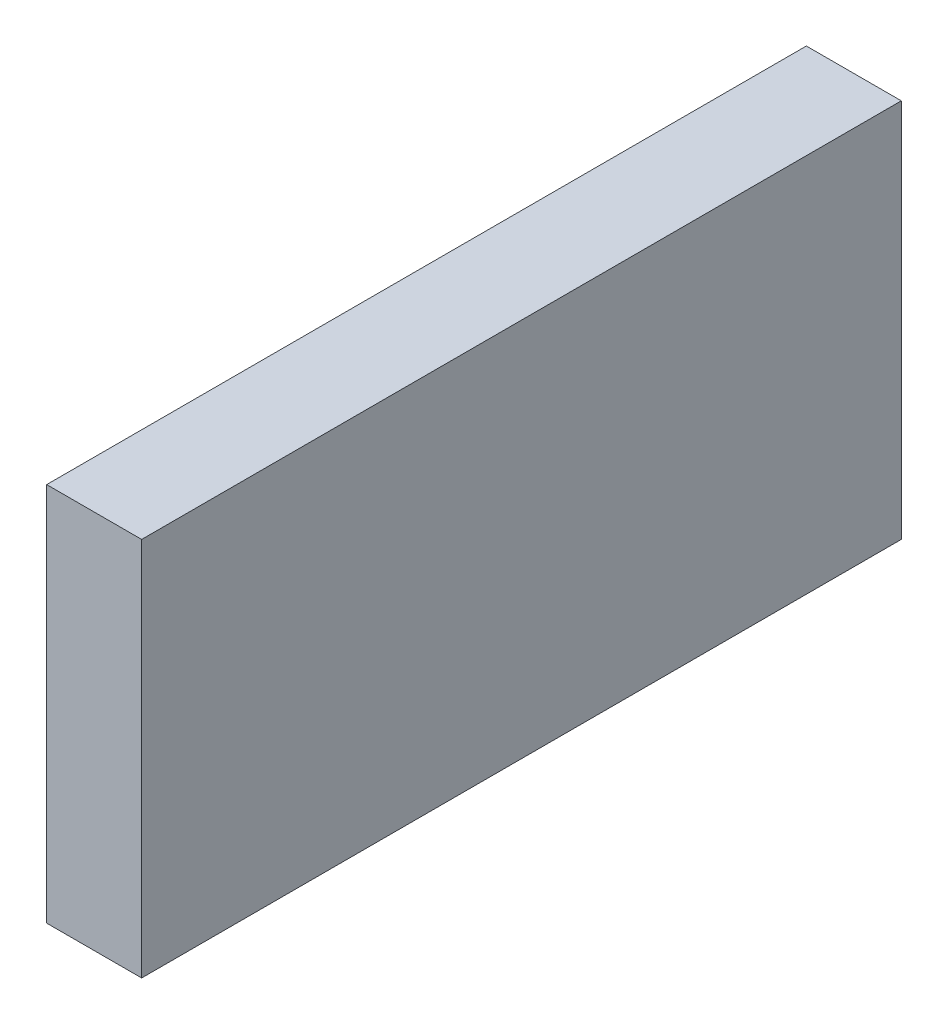
SolidWorks part; units mm, degrees
material "PE High Density"
ref_plane "Front Plane" through (0, 0, 0) normal (0, 0, 1) x (1, 0, 0)
ref_plane "Top Plane" through (0, 0, 0) normal (0, 1, 0) x (1, 0, 0)
ref_plane "Right Plane" through (0, 0, 0) normal (1, 0, 0) x (0, 0, -1)
sketch "Sketch1" plane through (0, 0, 0) normal (0, 0, 1) x (1, 0, 0)
  line L1 (0, 0) -> (6.35, 0)
  line L2 (0, 0) -> (0, 25.4)
  line L3 (0, 25.4) -> (6.35, 25.4)
  line L4 (6.35, 0) -> (6.35, 25.4)
  dimension "D1" = 25.4
  dimension "D2" = 6.35
extrude "Boss-Extrude1" add sketch "Sketch1" along normal blind 50.8
